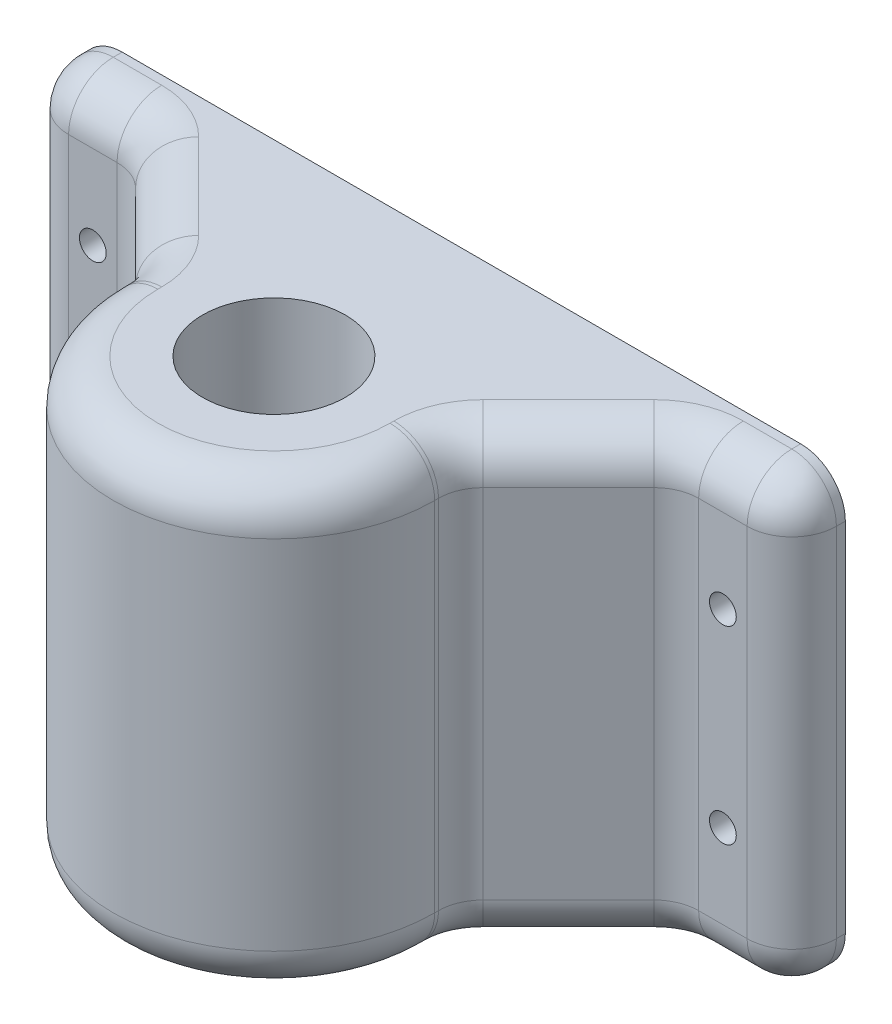
SolidWorks part; units mm, degrees
ref_plane "Front Plane" through (0, 0, 0) normal (0, 0, 1) x (1, 0, 0)
ref_plane "Top Plane" through (0, 0, 0) normal (0, 1, 0) x (1, 0, 0)
ref_plane "Right Plane" through (0, 0, 0) normal (1, 0, 0) x (0, 0, -1)
sketch "Sketch1" plane through (0, 0, 0) normal (0, 0, 1) x (1, 0, 0)
  line L0 (0, 0) -> (86, 0)
  line L1 (86, 0) -> (86, 50)
  line L2 (86, 50) -> (0, 50)
  line L3 (0, 50) -> (0, 0)
  dimension "D1" = 86
  dimension "D2" = 50
extrude "Boss-Extrude2" add sketch "Sketch1" along normal blind 6
sketch "Sketch2" plane through (0, 0, 0) normal (0, -1, 0) x (-1, 0, 0)
  line L0 (-43, -6) -> (-43, -35.2862) construction
  line L1 (0, -6) -> (-86, -6) construction
  line L2 (-61, -21) -> (-61, -6)
  line L3 (-61, -6) -> (-25, -6)
  line L4 (-25, -6) -> (-25, -21)
  arc A2 (-25, -21) -> (-61, -21) centre (-43, -21) cw
extrude "Boss-Extrude3" add sketch "Sketch2" against normal blind 50 contours L4 A2 L2 L3
sketch "Sketch4" plane through (0, 0, 0) normal (0, -1, 0) x (-1, 0, 0)
  line L0 (-25, -6) -> (-61, -6) construction
  line L1 (-43, -6) -> (-43, -21) construction
  circle A0 centre (-43, -21) radius 8
  dimension "D1" = 16
extrude "Cut-Extrude1" cut sketch "Sketch4" against normal blind 121
sketch "Sketch5" plane through (0, 0, 0) normal (0, -1, 0) x (-1, 0, 0)
  line L0 (-61, -6) -> (-73.5, -6)
  line L1 (-61, -6) -> (-86, -6) construction
  line L2 (-73.5, -6) -> (-61, -18.5)
  line L3 (-61, -21) -> (-61, -6) construction
  line L4 (-61, -18.5) -> (-61, -6)
extrude "Boss-Extrude5" add sketch "Sketch5" against normal blind 50
sketch "Sketch6" plane through (0, 0, 0) normal (0, -1, 0) x (-1, 0, 0)
  line L0 (-25, -6) -> (-12.5, -6)
  line L1 (0, -6) -> (-25, -6) construction
  line L2 (-12.5, -6) -> (-25, -18.5)
  line L3 (-25, -6) -> (-25, -21) construction
  line L4 (-25, -18.5) -> (-25, -6)
extrude "Boss-Extrude6" add sketch "Sketch6" against normal blind 50
fillet "Fillet1" radius 5 1 edges at (86, 25, 6)
fillet "Fillet2" radius 5 1 edges at (73.5, 25, 6)
fillet "Fillet3" radius 5 1 edges at (61, 25, 18.5)
fillet "Fillet4" radius 5 3 edges at (12.5, 25, 6) (25, 25, 18.5) (0, 25, 6)
fillet "Fillet5" radius 5 30 edges at (0, 50, 0.5) (1.4645, 50, 4.5355) (7.7145, 50, 6) (12.3423, 50, 6.3806) (18.75, 50, 12.25) (18.75, 0, 12.25) (24.6194, 50, 18.6577) (25, 50, 20.7855) (86, 50, 0.5) (84.5355, 50, 4.5355) (78.2855, 50, 6) (73.6577, 50, 6.3806) (67.25, 50, 12.25) (67.25, 0, 12.25) (61.3806, 50, 18.6577) (61, 50, 20.7855) (0, 0, 0.5) (1.4645, 0, 4.5355) (7.7145, 0, 6) (12.3423, 0, 6.3806) (24.6194, 0, 18.6577) (25, 0, 20.7855) (86, 0, 0.5) (84.5355, 0, 4.5355) (78.2855, 0, 6) (73.6577, 0, 6.3806) (61.3806, 0, 18.6577) (61, 0, 20.7855) (43, 50, 39) (43, 0, 39)
sketch "Sketch7" plane through (0, 0, 6) normal (0, 0, 1) x (1, 0, 0)
  line L0 (7.7145, 45) -> (7.7145, 5) construction
  line L1 (10.4289, 45) -> (5, 45) construction
  line L2 (5, 5) -> (10.4289, 5) construction
  line L3 (7.7145, 25) -> (5, 25) construction
  line L4 (5, 45) -> (5, 5) construction
  line L5 (5, 25) -> (10.4289, 25) construction
  line L6 (10.4289, 5) -> (10.4289, 45) construction
  circle A0 centre (7.7145, 35.6017) radius 1.5
  circle A1 centre (7.7145, 14.3983) radius 1.5
  dimension "D1" = 3
extrude "Cut-Extrude2" cut sketch "Sketch7" against normal blind 50
sketch "Sketch8" plane through (0, 0, 6) normal (0, 0, 1) x (1, 0, 0)
  line L3 (78.2855, 25) -> (81, 25) construction
  line L4 (81, 5) -> (81, 45) construction
  line L5 (81, 25) -> (75.5711, 25) construction
  line L6 (75.5711, 45) -> (75.5711, 5) construction
  line L7 (78.2855, 25) -> (78.2855, 35.6017) construction
  circle A0 centre (78.2855, 35.6017) radius 1.5
  circle A1 centre (78.2855, 14.3983) radius 1.5
  dimension "D2" = 3
  dimension "D1" = 10.6017
extrude "Cut-Extrude4" cut sketch "Sketch8" against normal blind 50
sketch "Sketch9" plane through (0, 0, 0) normal (0, 0, -1) x (-1, 0, 0)
  line L0 (-81, 0) -> (-81, 50)
  line L1 (-81, 50) -> (-5, 50)
  line L2 (-5, 50) -> (-5, 0)
  line L3 (-5, 0) -> (-81, 0)
extrude "Boss-Extrude7" add sketch "Sketch9" along normal blind 5
sketch "Sketch11" plane through (5, 0, 0) normal (-1, 0, 0) x (0, 0, 1)
  line L1 (0, 50) -> (-2.2607, -1.7776)
  line L2 (-2.2607, -1.7776) -> (-5.0227, -1.7776)
  line L3 (-5.0227, -1.7776) -> (-5, 50)
  line L4 (-5, 50) -> (0, 50)
extrude "Cut-Extrude5" cut sketch "Sketch11" against normal blind 121
